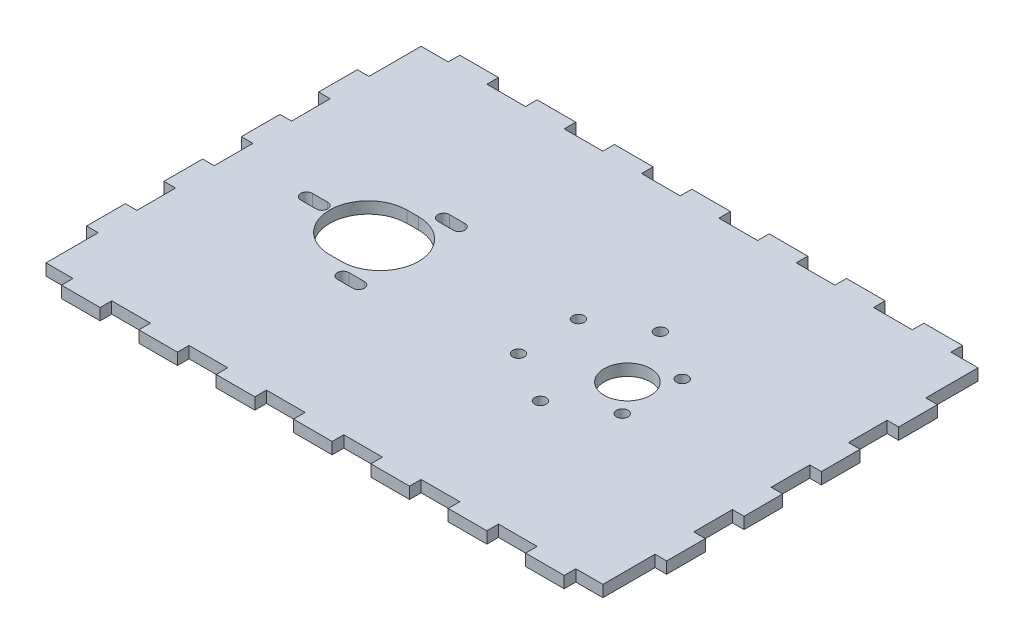
SolidWorks part; units mm, degrees
ref_plane "Front Plane" through (0, 0, 0) normal (0, 0, 1) x (1, 0, 0)
ref_plane "Top Plane" through (0, 0, 0) normal (0, 1, 0) x (1, 0, 0)
ref_plane "Right Plane" through (0, 0, 0) normal (1, 0, 0) x (0, 0, -1)
sketch "Sketch1" plane through (0, 0, 0) normal (0, 1, 0) x (1, 0, 0)
  line L1 (-75, -51.5) -> (75, -51.5)
  line L2 (-75, -51.5) -> (-75, 51.5)
  line L3 (-75, 51.5) -> (75, 51.5)
  line L4 (75, -51.5) -> (75, 51.5)
  line L5 (-75, -51.5) -> (75, 51.5) construction
  line L6 (-75, 51.5) -> (75, -51.5) construction
  point P0 (0, 0)
  dimension "D1" = 150
  dimension "D2" = 103
extrude "Boss-Extrude1" add sketch "Sketch1" along normal blind 3
sketch "Sketch2" plane through (0, 3, 0) normal (0, 1, 0) x (1, 0, 0)
  line L1 (75, -51.5) -> (65, -51.5)
  line L2 (75, -51.5) -> (75, -48.5)
  line L3 (75, -48.5) -> (65, -48.5)
  line L4 (65, -51.5) -> (65, -48.5)
  dimension "D1" = 10
  dimension "D2" = 3
extrude "Cut-Extrude1" cut sketch "Sketch2" against normal through all
pattern_linear "LPattern1" count 8 spacing 20 along (-1, 0, 0) of "Cut-Extrude1"
mirror "Mirror1" about plane through (0, 0, 0) normal (0, 0, 1) of "LPattern1", "Cut-Extrude1"
sketch "Sketch3" plane through (0, 3, 0) normal (0, 1, 0) x (1, 0, 0)
  line L0 (75, -48.5) -> (75, 48.5) construction
  line L1 (75, 45) -> (72, 45)
  line L2 (75, 45) -> (75, 35)
  line L3 (75, 35) -> (72, 35)
  line L4 (72, 45) -> (72, 35)
  line L5 (65, 51.5) -> (55, 51.5) construction
  dimension "D1" = 10
  dimension "D2" = 3
  dimension "D3" = 6.5
extrude "Cut-Extrude2" cut sketch "Sketch3" against normal through all
pattern_linear "LPattern2" count 5 spacing 20 along (0, 0, 1) of "Cut-Extrude2"
mirror "Mirror2" about plane through (0, 0, 0) normal (1, 0, 0) of "LPattern2", "Cut-Extrude2"
sketch "Sketch4" plane through (0, 3, 0) normal (0, 1, 0) x (1, 0, 0)
  line L0 (-65, -48.5) -> (-75, -48.5) construction
  line L1 (75, 48.5) -> (72, 48.5)
  line L2 (75, 48.5) -> (75, 45)
  line L3 (75, 45) -> (72, 45)
  line L4 (72, 48.5) -> (72, 45)
  line L5 (-75, 48.5) -> (-72, 48.5)
  line L6 (-75, 48.5) -> (-75, 45)
  line L7 (-75, 45) -> (-72, 45)
  line L8 (-72, 48.5) -> (-72, 45)
  line L9 (-75, -45) -> (-72, -45)
  line L10 (-75, -45) -> (-75, -48.5)
  line L11 (-75, -48.5) -> (-72, -48.5)
  line L12 (-72, -45) -> (-72, -48.5)
  line L13 (75, -48.5) -> (65, -48.5) construction
  line L14 (72, -45) -> (75, -45)
  line L15 (72, -45) -> (72, -48.5)
  line L16 (72, -48.5) -> (75, -48.5)
  line L17 (75, -45) -> (75, -48.5)
extrude "Cut-Extrude3" cut sketch "Sketch4" against normal through all
sketch "Sketch7" plane through (0, 3, 0) normal (0, 1, 0) x (1, 0, 0)
  line L0 (-72, 0) -> (72, 0) construction
  line L1 (-34.1516, 0) -> (-37.1516, 0) construction
  line L2 (-34.1516, -10) -> (-37.1516, -10)
  line L3 (22.8484, 0) -> (22.8484, 44.9782) construction
  line L4 (-34.1516, 10) -> (-37.1516, 10)
  line L5 (-49.1516, 0) -> (-53.1516, 0) construction
  line L6 (-49.1516, -1.5) -> (-53.1516, -1.5)
  line L7 (-49.1516, 1.5) -> (-53.1516, 1.5)
  line L8 (-34.1516, 0) -> (-49.1516, 0) construction
  line L9 (-34.1516, 0) -> (-26.6516, 12.9904) construction
  line L10 (-26.6516, 12.9686) -> (-30.6516, 12.9686) construction
  line L11 (-26.6516, 11.4686) -> (-30.6516, 11.4686)
  line L12 (-26.6516, 14.4686) -> (-30.6516, 14.4686)
  line L13 (-26.6516, -13.0122) -> (-30.6516, -13.0122) construction
  line L14 (-26.6516, -14.5122) -> (-30.6516, -14.5122)
  line L15 (-26.6516, -11.5122) -> (-30.6516, -11.5122)
  line L16 (72, 0) -> (-72, 0) construction
  line L19 (72, 5) -> (72, -5) construction
  line L20 (-72, 5) -> (-72, -5) construction
  circle A0 centre (29.8484, 0) radius 6
  circle A1 centre (22.8484, 15.5) radius 1.5
  circle A2 centre (36.2718, 7.75) radius 1.5
  circle A3 centre (36.2718, -7.75) radius 1.5
  circle A4 centre (22.8484, -15.5) radius 1.5
  circle A5 centre (9.425, -7.75) radius 1.5
  circle A6 centre (9.425, 7.75) radius 1.5
  arc A7 (-34.1516, -10) -> (-34.1516, 10) centre (-34.1516, 0) ccw
  arc A8 (-37.1516, 10) -> (-37.1516, -10) centre (-37.1516, 0) ccw
  arc A9 (-49.1516, -1.5) -> (-49.1516, 1.5) centre (-49.1516, 0) ccw
  arc A10 (-53.1516, 1.5) -> (-53.1516, -1.5) centre (-53.1516, 0) ccw
  arc A11 (-26.6516, 11.4686) -> (-26.6516, 14.4686) centre (-26.6516, 12.9686) ccw
  arc A12 (-30.6516, 14.4686) -> (-30.6516, 11.4686) centre (-30.6516, 12.9686) ccw
  arc A13 (-26.6516, -14.5122) -> (-26.6516, -11.5122) centre (-26.6516, -13.0122) ccw
  arc A14 (-30.6516, -11.5122) -> (-30.6516, -14.5122) centre (-30.6516, -13.0122) ccw
  point P8 (29.8484, 0)
  point P9 (22.8484, 0)
  point P10 (22.8484, 15.5)
  point P27 (22.8484, 0)
  point P30 (-35.6516, 0)
  point P36 (-49.1516, 0)
  point P39 (-51.1516, 0)
  point P42 (-34.1516, 0)
  point P48 (-26.6516, 12.9904)
  point P49 (-26.6516, -12.9904)
  point P53 (-23.4817, 7.4782)
  point P55 (-28.6516, 12.9686)
  point P62 (-28.6516, -13.0122)
  dimension "D2" = 12
  dimension "D3" = 7
  dimension "D9" = 60
  dimension "D5" = 3
  dimension "D10" = 10
  dimension "D15" = 1.5
  dimension "D16" = 4
  dimension "D17" = 3
  dimension "D4" = 15.5
  dimension "D6" = 6
  dimension "D7" = 64
  dimension "D12" = 10
  dimension "D13" = 3
  dimension "D14" = 12
  dimension "D18" = 120
  dimension "D19" = 15
extrude "Cut-Extrude4" cut sketch "Sketch7" against normal through all
hole_wizard "M3x0.5 Tapped Hole3" positions "Sketch11" profile "Sketch10" hole size "Ø3.0" standard "ANSI Metric"
sketch "Sketch11" plane through (0, 3, 0) normal (0, 1, 0) x (1, 0, 0)
  point P0 (22.8484, 15.5)
  point P7 (36.2718, -7.75)
  point P10 (22.8484, -15.5)
  point P13 (9.425, -7.75)
  point P16 (9.425, 7.75)
  point P27 (36.2718, 7.75)
sketch "Sketch10" plane through (22.8484, 3, -15.5) normal (1, 0, 0) x (0, 0, 1)
  line L0 (0, 0) -> (0, 10.9013)
  line L1 (0, 10.9013) -> (1.5, 10)
  line L2 (1.5, 10) -> (1.5, 0)
  line L5 (1.5, 0) -> (0, 0)
  line L10 (0, 10.9013) -> (-1.5, 10) construction
  line L11 (0, -6.35) -> (0, 107.95) construction
  dimension "Hole Dia." = 3
  dimension "Hole Depth" = 10
  dimension "Drill Angle" = 118
